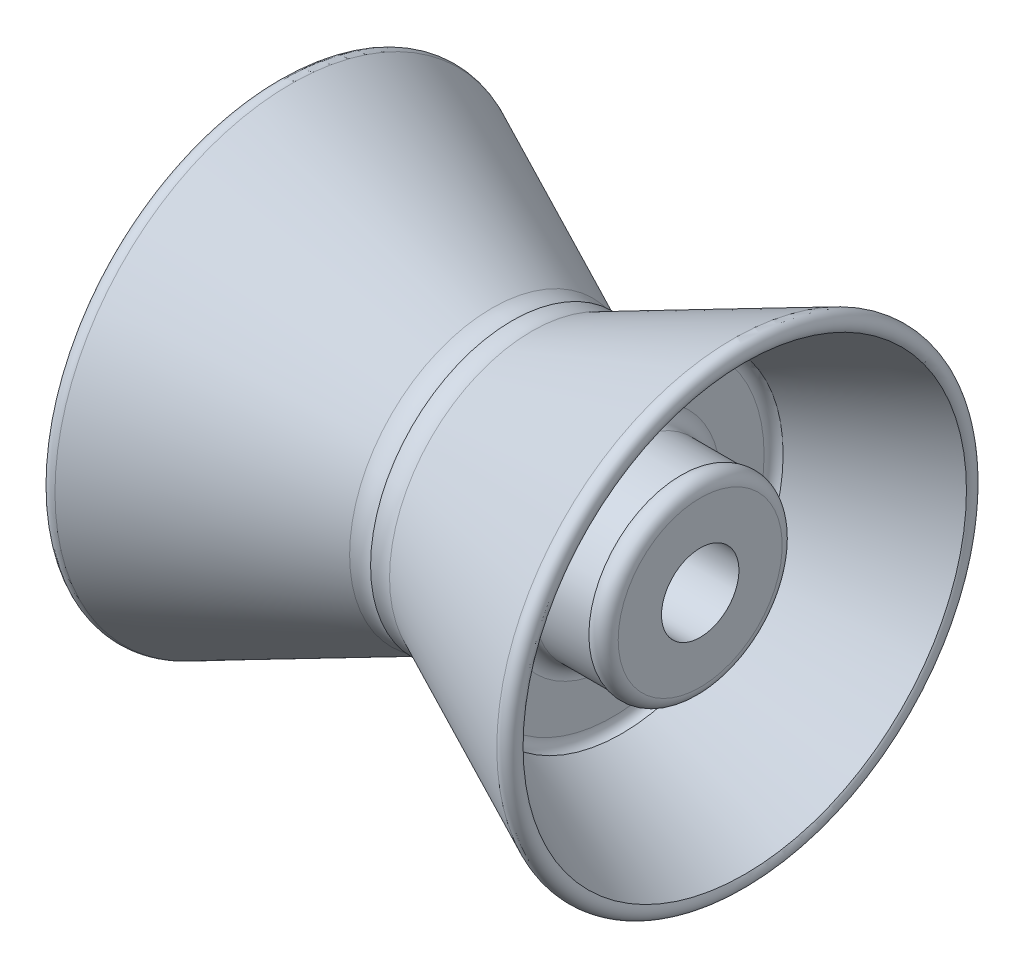
SolidWorks part; units mm, degrees
ref_plane "Front Plane" through (0, 0, 0) normal (0, 0, 1) x (1, 0, 0)
ref_plane "Top Plane" through (0, 0, 0) normal (0, 1, 0) x (1, 0, 0)
ref_plane "Right Plane" through (0, 0, 0) normal (1, 0, 0) x (0, 0, -1)
sketch "Sketch1" plane through (0, 0, 0) normal (0, 1, 0) x (1, 0, 0)
  line L0 (-137.8575, 0) -> (174.5995, 0) construction
  line L1 (0, 106.0253) -> (0, -86.8327) construction
  line L2 (-39.2434, 18.4958) -> (-89.9458, 18.4958)
  line L3 (-89.9458, 18.4958) -> (-89.9458, 39.1901)
  line L4 (-80.8782, 44.1419) -> (-54.4687, 44.1419)
  line L5 (-48.0727, 51.5696) -> (-48.0727, 72.4083)
  line L6 (-52.4246, 77.1567) -> (-111.2462, 105.9504)
  line L7 (-105.5777, 112.8466) -> (-9.5424, 68.0646)
  line L8 (-39.2434, 0) -> (-39.2434, 50.6412)
  line L9 (-31.9229, 56.7268) -> (-7.6445, 45.4056)
  line L10 (-89.9458, 18.4958) -> (-89.9458, 0)
  line L11 (89.9458, 18.4958) -> (89.9458, 0)
  line L12 (31.9229, 56.7268) -> (7.6445, 45.4056)
  line L13 (39.2434, 0) -> (39.2434, 50.6412)
  line L14 (105.5777, 112.8466) -> (9.5424, 68.0646)
  line L15 (52.4246, 77.1567) -> (111.2462, 105.9504)
  line L16 (48.0727, 51.5696) -> (48.0727, 72.4083)
  line L17 (80.8782, 44.1419) -> (54.4687, 44.1419)
  line L18 (89.9458, 18.4958) -> (89.9458, 39.1901)
  line L19 (39.2434, 18.4958) -> (89.9458, 18.4958)
  arc A0 (-89.9458, 39.1901) -> (-80.8782, 44.1419) centre (-84.0599, 39.1901) cw
  arc A1 (-54.4687, 44.1419) -> (-48.0727, 51.5696) centre (-54.4687, 50.6096) ccw
  arc A2 (-48.0727, 72.4083) -> (-52.4246, 77.1567) centre (-52.8392, 72.4083) ccw
  arc A3 (-105.5777, 112.8466) -> (-111.2462, 105.9504) centre (-107.5254, 108.6698) ccw
  arc A4 (-9.5424, 68.0646) -> (0, 67.5872) centre (-4.1843, 79.555) ccw
  arc A5 (-39.2434, 50.6412) -> (-31.9229, 56.7268) centre (-33.0536, 50.6412) cw
  arc A6 (-7.6445, 45.4056) -> (0, 45.7885) centre (-4.1843, 52.8261) ccw
  arc A7 (7.6445, 45.4056) -> (0, 45.7885) centre (4.1843, 52.8261) cw
  arc A8 (39.2434, 50.6412) -> (31.9229, 56.7268) centre (33.0536, 50.6412) ccw
  arc A9 (9.5424, 68.0646) -> (0, 67.5872) centre (4.1843, 79.555) cw
  arc A10 (105.5777, 112.8466) -> (111.2462, 105.9504) centre (107.5254, 108.6698) cw
  arc A11 (48.0727, 72.4083) -> (52.4246, 77.1567) centre (52.8392, 72.4083) cw
  arc A12 (54.4687, 44.1419) -> (48.0727, 51.5696) centre (54.4687, 50.6096) cw
  arc A13 (89.9458, 39.1901) -> (80.8782, 44.1419) centre (84.0599, 39.1901) ccw
  dimension "D2" = 4.6086
  dimension "D1" = 65
revolve "Revolve2" add sketch "Sketch1" angle 360 about L0
